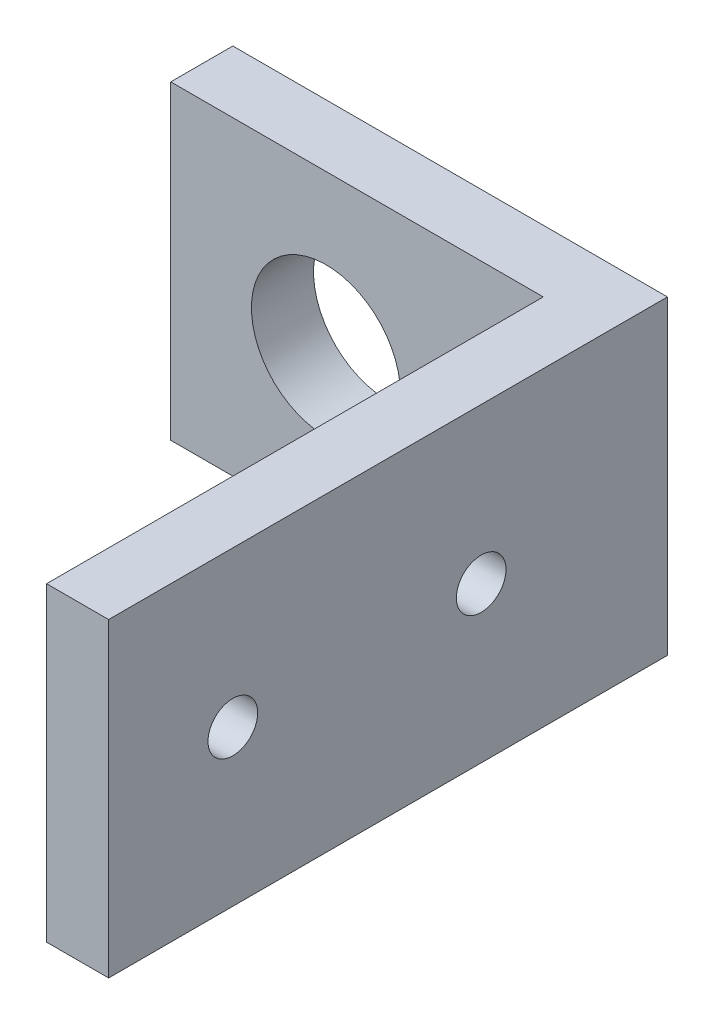
SolidWorks part; units mm, degrees
ref_plane "Front Plane" through (0, 0, 0) normal (0, 0, 1) x (1, 0, 0)
ref_plane "Top Plane" through (0, 0, 0) normal (0, 1, 0) x (1, 0, 0)
ref_plane "Right Plane" through (0, 0, 0) normal (1, 0, 0) x (0, 0, -1)
sketch "Sketch1" plane through (0, 0, 0) normal (0, 0, 1) x (1, 0, 0)
  line L1 (0, 0) -> (35, 0)
  line L2 (0, 0) -> (0, 25)
  line L3 (0, 25) -> (35, 25)
  line L4 (35, 0) -> (35, 25)
  dimension "D1" = 25
  dimension "D2" = 35
extrude "Boss-Extrude1" add sketch "Sketch1" along normal blind 5
sketch "Sketch2" plane through (0, 0, 5) normal (0, 0, 1) x (1, 0, 0)
  line L0 (35, 25) -> (0, 25) construction
  line L1 (30, 25) -> (35, 25)
  line L2 (30, 25) -> (30, 0)
  line L3 (30, 0) -> (35, 0)
  line L4 (35, 25) -> (35, 0)
  dimension "D1" = 5
extrude "Boss-Extrude2" add sketch "Sketch2" along normal blind 40
sketch "Sketch3" plane through (0, 0, 5) normal (0, 0, 1) x (1, 0, 0)
  line L0 (0, 25) -> (0, 0) construction
  line L1 (0, 0) -> (30, 0) construction
  circle A0 centre (12.5, 12.5) radius 6
  dimension "D1" = 12
  dimension "D2" = 12.5
  dimension "D3" = 12.5
extrude "Cut-Extrude1" cut sketch "Sketch3" against normal through all
sketch "Sketch4" plane through (30, 0, 0) normal (-1, 0, 0) x (0, 0, 1)
  line L0 (45, 0) -> (5, 0) construction
  line L1 (5, 25) -> (5, 0) construction
  circle A0 centre (15, 12.5) radius 2
  circle A1 centre (35, 12.5) radius 2
  dimension "D1" = 4
  dimension "D2" = 4
  dimension "D3" = 12.5
  dimension "D4" = 12.5
  dimension "D5" = 10
  dimension "D6" = 20
extrude "Cut-Extrude2" cut sketch "Sketch4" against normal through all
